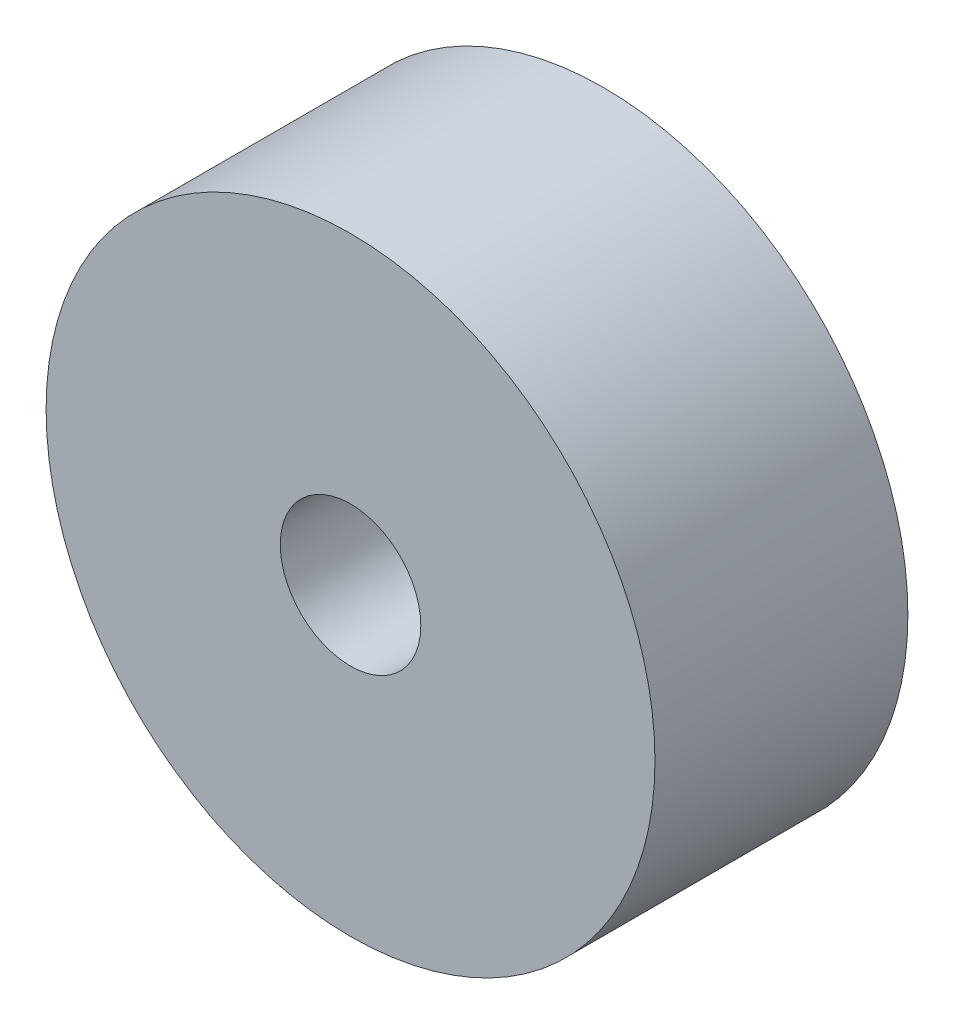
SolidWorks part; units mm, degrees
ref_plane "前视基准面" through (0, 0, 0) normal (0, 0, 1) x (1, 0, 0)
ref_plane "上视基准面" through (0, 0, 0) normal (0, 1, 0) x (1, 0, 0)
ref_plane "右视基准面" through (0, 0, 0) normal (1, 0, 0) x (0, 0, -1)
sketch "草图1" plane through (0, 0, 0) normal (0, 0, 1) x (1, 0, 0)
  circle A0 centre (0, 0) radius 32.5
  circle A1 centre (0, 0) radius 7.5
extrude "凸台-拉伸1" add sketch "草图1" along normal blind 27 contours A0 A1
